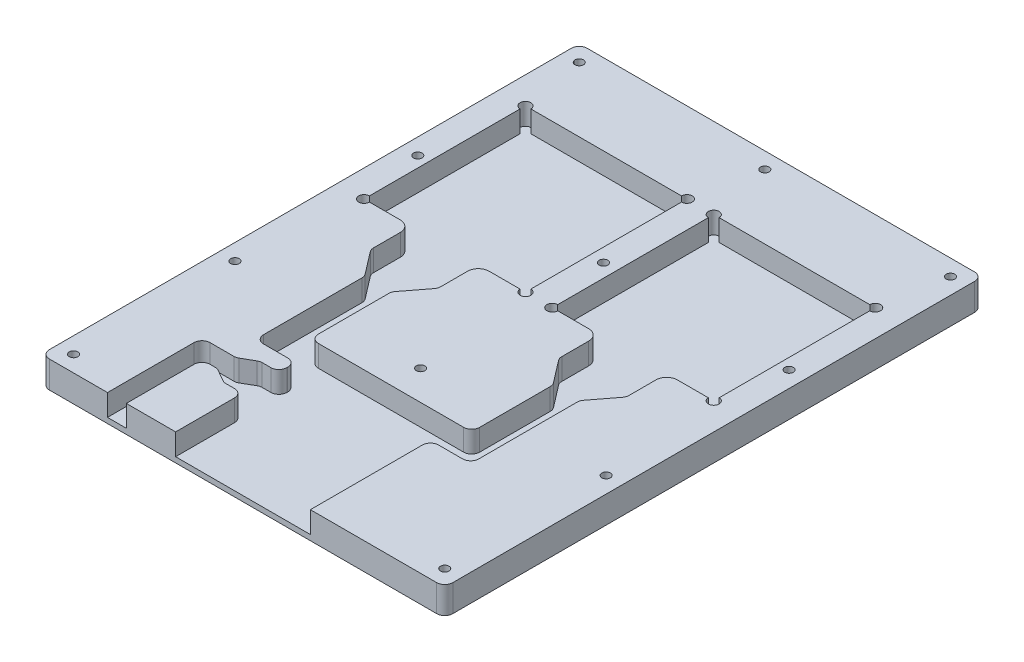
SolidWorks part; units mm, degrees
ref_plane "Front" through (0, 0, 0) normal (0, 0, 1) x (1, 0, 0)
ref_plane "Top" through (0, 0, 0) normal (0, 1, 0) x (1, 0, 0)
ref_plane "Right" through (0, 0, 0) normal (1, 0, 0) x (0, 0, -1)
sketch "Эскиз1" plane through (0, 0, 0) normal (0, 1, 0) x (1, 0, 0)
  line L1 (-72, 100) -> (72, 100)
  line L2 (-75, 97) -> (-75, -97)
  line L3 (-72, -100) -> (72, -100)
  line L4 (75, 97) -> (75, -97)
  line L5 (-75, 100) -> (75, -100) construction
  line L6 (-75, -100) -> (75, 100) construction
  arc A0 (75, -97) -> (72, -100) centre (72, -97) cw
  arc A1 (-72, -100) -> (-75, -97) centre (-72, -97) cw
  arc A2 (75, 97) -> (72, 100) centre (72, 97) ccw
  arc A3 (-72, 100) -> (-75, 97) centre (-72, 97) ccw
  point P0 (0, 0)
  dimension "D1" = 3
extrude "Бобышка-Вытянуть1" add sketch "Эскиз1" along normal blind 10
sketch "Эскиз2" plane through (0, 10, 0) normal (0, 1, 0) x (1, 0, 0)
  line L0 (-75, 40) -> (75, 40) construction
  line L1 (0, 100) -> (0, -100) construction
  line L2 (72, 100) -> (-72, 100) construction
  line L3 (-72, -100) -> (72, -100) construction
  line L4 (-75, 97) -> (-75, -97) construction
  line L5 (75, -97) -> (75, 97) construction
  line L6 (22.5, 6) -> (22.5, -3.9822)
  line L7 (-63, 70) -> (-7, 70)
  line L8 (-65, 68) -> (-65, 12)
  line L9 (-63, 10) -> (-51.5, 10)
  line L10 (-5, 68) -> (-5, 12)
  line L11 (-72, -100) -> (72, -100) construction
  line L12 (47.5, 6) -> (47.5, -3.9822)
  line L13 (18.5, 10) -> (7, 10)
  line L14 (5, 68) -> (5, 12)
  line L15 (63, 10) -> (51.5, 10)
  line L16 (65, 68) -> (65, 12)
  line L17 (63, 70) -> (7, 70)
  line L18 (-18.5, 10) -> (-7, 10)
  line L19 (-35, 70) -> (-35, 40) construction
  line L20 (-47.5, 6) -> (-47.5, -3.9822)
  line L21 (-25.047, -100) -> (25.047, -100)
  line L22 (-22.5, 6) -> (-22.5, -3.9822)
  line L23 (35, 70) -> (35, 40) construction
  line L24 (-25.047, -58.3575) -> (-25.047, -58.6075)
  line L25 (-40.6193, -13.9739) -> (-46.8807, -5.8077)
  line L26 (-29.3807, -13.9739) -> (-23.1193, -5.8077)
  line L27 (-27, -44.9946) -> (27, -44.9946)
  line L28 (-37, -55.3575) -> (-28.047, -55.3575)
  line L29 (37, -55.3575) -> (28.047, -55.3575)
  line L30 (25.047, -58.3575) -> (25.047, -78.1075)
  line L31 (29.3807, -13.9739) -> (23.1193, -5.8077)
  line L32 (40.6193, -13.9739) -> (46.8807, -5.8077)
  line L33 (40, -15.7993) -> (40, -52.3575)
  line L34 (-40, -15.7993) -> (-40, -52.3575)
  line L35 (-25.047, -78.1075) -> (-25.047, -100)
  line L36 (-30, -15.7993) -> (-30, -41.9946)
  line L37 (25.047, -78.1075) -> (25.047, -100)
  line L40 (30, -15.7993) -> (30, -41.9946)
  line L52 (-28.047, -75.1075) -> (-31.2478, -75.1075)
  line L53 (-32.7403, -74.7099) -> (-37.0206, -72.2551)
  line L54 (-32.7403, -62.0051) -> (-37.0206, -64.4599)
  line L55 (-28.047, -61.6075) -> (-31.2478, -61.6075)
  line L56 (-50.3807, -67.8575) -> (-50.3807, -100)
  line L57 (-38.5131, -64.8575) -> (-47.3807, -64.8575)
  line L58 (-43.3807, -74.8575) -> (-43.3807, -100)
  line L59 (-43.3807, -100) -> (-50.3807, -100)
  line L60 (-38.5131, -71.8575) -> (-40.3807, -71.8575)
  arc A0 (-65, 12) -> (-63, 10) centre (-65, 10) ccw
  arc A1 (-65, 68) -> (-63, 70) centre (-65, 70) cw
  arc A2 (-5, 12) -> (-7, 10) centre (-5, 10) cw
  arc A3 (-5, 68) -> (-7, 70) centre (-5, 70) ccw
  arc A4 (5, 12) -> (7, 10) centre (5, 10) ccw
  arc A5 (65, 12) -> (63, 10) centre (65, 10) cw
  arc A6 (65, 68) -> (63, 70) centre (65, 70) ccw
  arc A7 (5, 68) -> (7, 70) centre (5, 70) cw
  arc A8 (47.5, -3.9822) -> (46.8807, -5.8077) centre (44.5, -3.9822) cw
  arc A9 (40, -52.3575) -> (37, -55.3575) centre (37, -52.3575) cw
  arc A10 (28.047, -55.3575) -> (25.047, -58.3575) centre (28.047, -58.3575) ccw
  arc A11 (-25.047, -58.3575) -> (-28.047, -55.3575) centre (-28.047, -58.3575) ccw
  arc A12 (-37, -55.3575) -> (-40, -52.3575) centre (-37, -52.3575) cw
  arc A13 (40.6193, -13.9739) -> (40, -15.7993) centre (43, -15.7993) ccw
  arc A14 (22.5, -3.9822) -> (23.1193, -5.8077) centre (25.5, -3.9822) ccw
  arc A15 (30, -15.7993) -> (29.3807, -13.9739) centre (27, -15.7993) ccw
  arc A16 (51.5, 10) -> (47.5, 6) centre (51.5, 6) ccw
  arc A17 (22.5, 6) -> (18.5, 10) centre (18.5, 6) ccw
  arc A18 (-18.5, 10) -> (-22.5, 6) centre (-18.5, 6) ccw
  arc A19 (-51.5, 10) -> (-47.5, 6) centre (-51.5, 6) cw
  arc A20 (-30, -15.7993) -> (-29.3807, -13.9739) centre (-27, -15.7993) cw
  arc A21 (-22.5, -3.9822) -> (-23.1193, -5.8077) centre (-25.5, -3.9822) cw
  arc A22 (-47.5, -3.9822) -> (-46.8807, -5.8077) centre (-44.5, -3.9822) ccw
  arc A23 (-40.6193, -13.9739) -> (-40, -15.7993) centre (-43, -15.7993) cw
  arc A24 (30, -41.9946) -> (27, -44.9946) centre (27, -41.9946) cw
  arc A25 (-30, -41.9946) -> (-27, -44.9946) centre (-27, -41.9946) ccw
  arc A36 (-50.3807, -67.8575) -> (-47.3807, -64.8575) centre (-47.3807, -67.8575) cw
  arc A37 (-43.3807, -74.8575) -> (-40.3807, -71.8575) centre (-40.3807, -74.8575) cw
  arc A38 (-25.047, -78.1075) -> (-28.047, -75.1075) centre (-28.047, -78.1075) ccw
  arc A39 (-32.7403, -62.0051) -> (-31.2478, -61.6075) centre (-31.2478, -64.6075) cw
  arc A40 (-38.5131, -64.8575) -> (-37.0206, -64.4599) centre (-38.5131, -61.8575) ccw
  arc A41 (-38.5131, -71.8575) -> (-37.0206, -72.2551) centre (-38.5131, -74.8575) cw
  arc A42 (-31.2478, -75.1075) -> (-32.7403, -74.7099) centre (-31.2478, -72.1075) cw
  arc A43 (-25.047, -58.6075) -> (-28.047, -61.6075) centre (-28.047, -58.6075) cw
  point P9 (0, 40)
  point P21 (-35, 10)
  point P60 (40, -55.3575)
  point P74 (-40, -55.3575)
  point P78 (47.5, -5)
  point P82 (40, -14.7815)
  point P85 (47.5, 10)
  point P88 (22.5, 10)
  point P91 (-22.5, 10)
  point P94 (-47.5, 10)
  point P96 (22.5, -5)
  point P99 (30, -14.7815)
  point P102 (-30, -14.7815)
  point P105 (-22.5, -5)
  point P108 (-47.5, -5)
  point P111 (-40, -14.7815)
  point P186 (-25.047, -75.1075)
  point P187 (-25.047, -61.6075)
  point P188 (-32.047, -61.6075)
  point P189 (-37.7139, -64.8575)
  point P190 (-37.7139, -71.8575)
  point P191 (-32.047, -75.1075)
  dimension "D1" = 3
  dimension "D2" = 4
  dimension "D3" = 3
extrude "Вырез-Вытянуть1" cut sketch "Эскиз2" against normal blind 8
sketch "Эскиз3" plane through (0, 10, 0) normal (0, 1, 0) x (1, 0, 0)
  line L0 (-75, 0) -> (75, 0) construction
  line L2 (0, 94) -> (-69, 94) construction
  line L3 (0, 94) -> (69, 94) construction
  line L4 (-75, 97) -> (-75, -97) construction
  line L5 (75, -97) -> (75, 97) construction
  line L6 (0, -34) -> (69, -34) construction
  line L7 (0, 34) -> (-69, 34) construction
  line L9 (0, -34) -> (-69, -34) construction
  line L10 (0, 34) -> (69, 34) construction
  line L12 (0, -94) -> (69, -94) construction
  line L13 (0, -94) -> (-69, -94) construction
  circle A0 centre (-69, 94) radius 1.5875
  circle A1 centre (0, 94) radius 1.5875
  circle A2 centre (69, 94) radius 1.5875
  circle A3 centre (-69, -34) radius 1.5875
  circle A4 centre (69, -34) radius 1.5875
  circle A5 centre (0, -34) radius 1.5875
  circle A6 centre (69, -94) radius 1.5875
  circle A8 centre (-69, -94) radius 1.5875
  circle A11 centre (0, 34) radius 1.5875
  circle A16 centre (69, 34) radius 1.5875
  circle A17 centre (-69, 34) radius 1.5875
extrude "Вырез-Вытянуть2" cut sketch "Эскиз3" against normal through all
